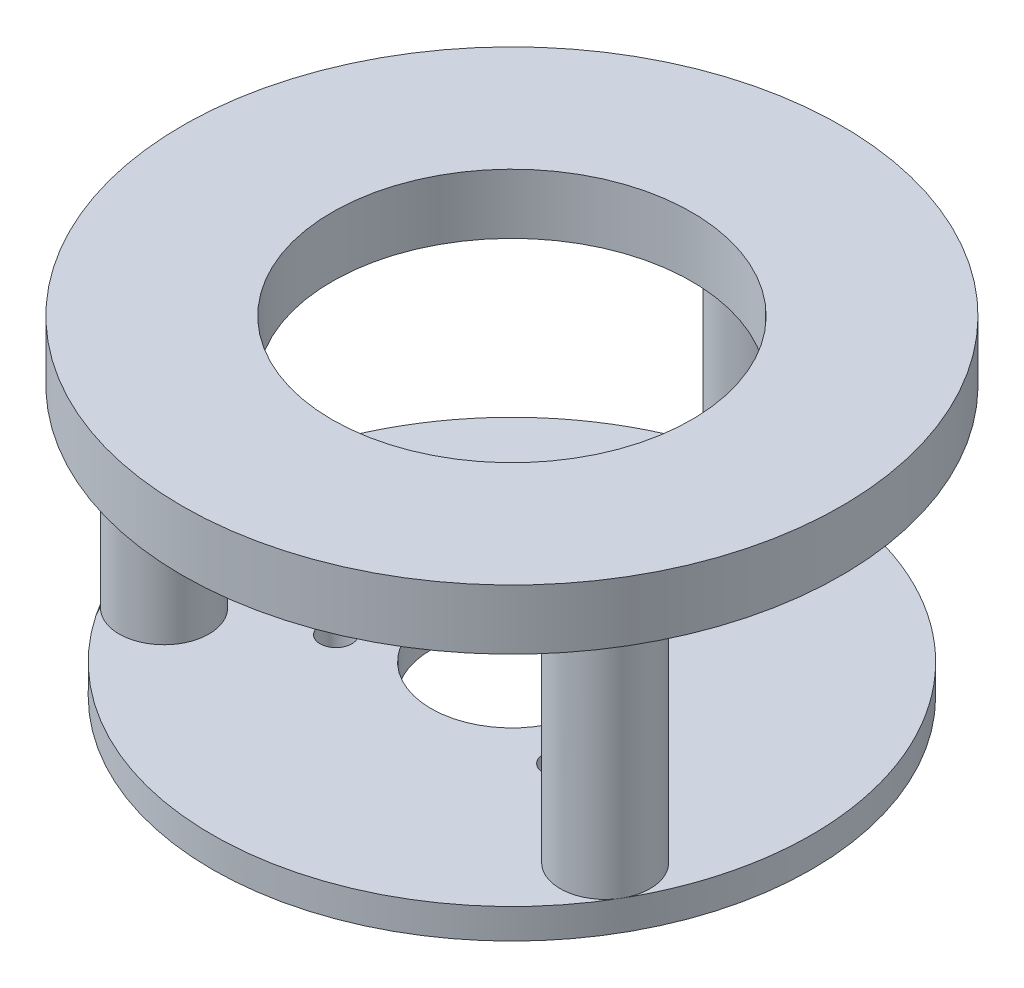
SolidWorks part; units mm, degrees
ref_plane "Front Plane" through (0, 0, 0) normal (0, 0, 1) x (1, 0, 0)
ref_plane "Top Plane" through (0, 0, 0) normal (0, 1, 0) x (1, 0, 0)
ref_plane "Right Plane" through (0, 0, 0) normal (1, 0, 0) x (0, 0, -1)
sketch "Sketch1" plane through (0, 0, 0) normal (0, 1, 0) x (1, 0, 0)
  line L0 (0, 0) -> (0, 21.5) construction
  line L1 (0, 0) -> (23.0125, 0) construction
  circle A0 centre (0, 0) radius 13.5
  circle A1 centre (0, 0) radius 23.0125 construction
  circle A2 centre (0, 0) radius 21.5 construction
  circle A3 centre (0, 0) radius 50
  circle A4 centre (0, 21.5) radius 2.65
  circle A5 centre (23.0125, 0) radius 1.65
  circle A6 centre (-23.0125, 0) radius 1.65
  circle A7 centre (18.6195, -10.75) radius 2.65
  circle A8 centre (-18.6195, -10.75) radius 2.65
  circle A9 centre (10.48, -15.75) radius 1.95 construction
  circle A10 centre (-10.48, -15.75) radius 1.95 construction
  dimension "D1" = 27
  dimension "D2" = 46.025
  dimension "D3" = 43
  dimension "D4" = 100
  dimension "D5" = 5.3
  dimension "D6" = 3.3
  dimension "D9" = 3.9
  dimension "D10" = 15.75
  dimension "D11" = 10.48
  dimension "D7" = 2
  dimension "D8" = 3
extrude "Boss-Extrude1" add sketch "Sketch1" along normal blind 5
ref_plane "Plane1" through (0, 0, 0) normal (0, -1, 0) x (-1, 0, 0)
ref_plane "Plane2" through (0, 5, 0) normal (0, 1, 0) x (1, 0, 0)
sketch "Sketch3" plane through (0, 5, 0) normal (0, 1, 0) x (1, 0, 0)
  line L0 (0, 50) -> (0, 42.5) construction
  circle A0 centre (0, 0) radius 50 construction
  circle A1 centre (0, 0) radius 50 construction
  circle A2 centre (0, 42.5) radius 7.5
  circle A3 centre (36.8061, -21.25) radius 7.5
  circle A4 centre (-36.8061, -21.25) radius 7.5
  dimension "D1" = 15
  dimension "D2" = 3
extrude "Boss-Extrude2" add sketch "Sketch3" along normal blind 40
ref_plane "Plane3" through (0, 45, 0) normal (0, 1, 0) x (1, 0, 0)
sketch "Sketch4" plane through (0, 45, 0) normal (0, 1, 0) x (1, 0, 0)
  circle A0 centre (0, 0) radius 55
  circle A1 centre (0, 0) radius 30
  dimension "D1" = 110
  dimension "D2" = 60
extrude "Boss-Extrude3" add sketch "Sketch4" along normal blind 10
ref_plane "Plane4" through (0, 0, 0) normal (0, -1, 0) x (-1, 0, 0)
sketch "Sketch5" plane through (0, 0, 0) normal (0, -1, 0) x (-1, 0, 0)
  line L0 (-26.4766, 0) -> (-24.7446, -3)
  line L1 (26.4766, 0) -> (24.7446, 3)
  line L2 (24.7446, 3) -> (21.2804, 3)
  line L3 (21.2804, 3) -> (19.5484, 0)
  line L4 (19.5484, 0) -> (21.2804, -3)
  line L5 (21.2804, -3) -> (24.7446, -3)
  line L6 (24.7446, -3) -> (26.4766, 0)
  line L7 (-24.7446, -3) -> (-21.2804, -3)
  line L8 (-21.2804, -3) -> (-19.5484, 0)
  line L9 (-19.5484, 0) -> (-21.2804, 3)
  line L10 (-21.2804, 3) -> (-24.7446, 3)
  line L11 (-24.7446, 3) -> (-26.4766, 0)
  circle A0 centre (23.0125, 0) radius 1.65 construction
  circle A1 centre (23.0125, 0) radius 1.65 construction
  circle A2 centre (0, 0) radius 23.0125 construction
  circle A3 centre (23.0125, 0) radius 3 construction
  dimension "D1" = 6
  dimension "D2" = 2
extrude "Cut-Extrude1" cut sketch "Sketch5" against normal blind 3.5
